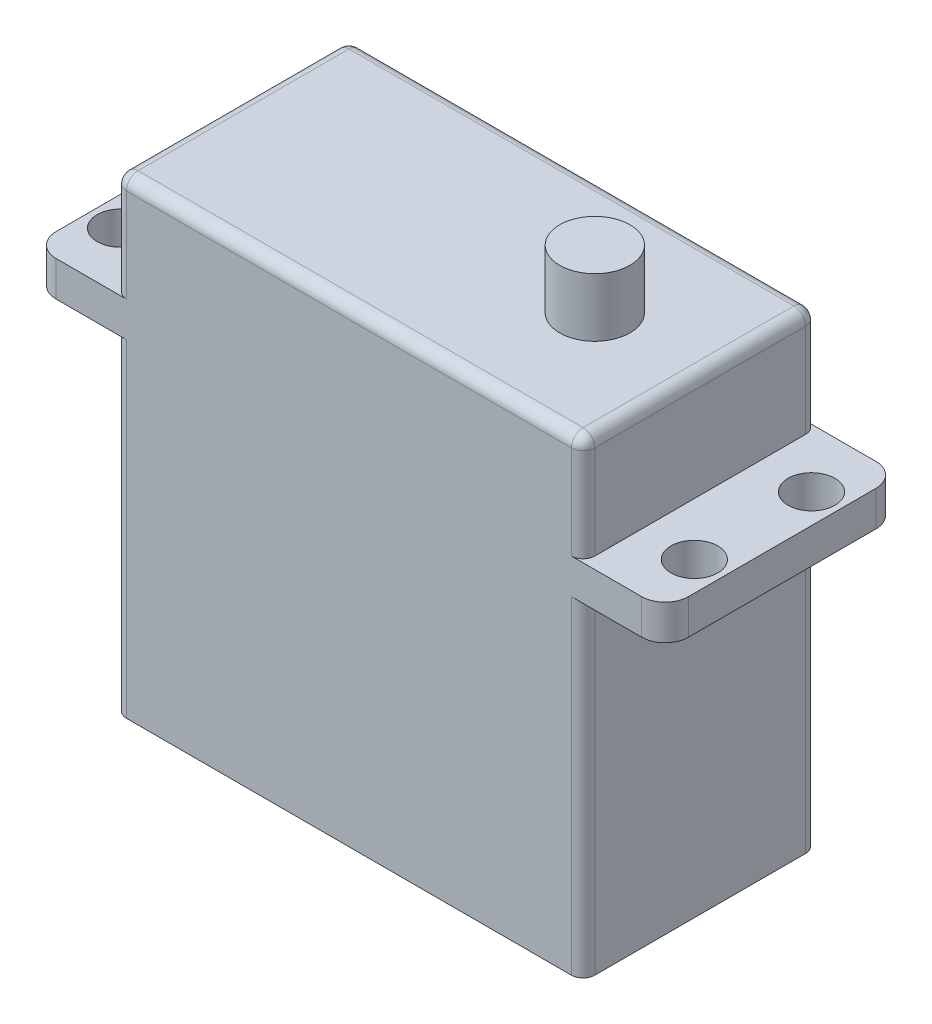
SolidWorks part; units mm, degrees
ref_plane "Front Plane" through (0, 0, 0) normal (0, 0, 1) x (1, 0, 0)
ref_plane "Top Plane" through (0, 0, 0) normal (0, 1, 0) x (1, 0, 0)
ref_plane "Right Plane" through (0, 0, 0) normal (1, 0, 0) x (0, 0, -1)
sketch "Sketch1" plane through (0, 0, 0) normal (0, 0, 1) x (1, 0, 0)
  line L0 (20, 14) -> (27, 14)
  line L2 (-20, 14) -> (-20, -14)
  line L3 (-20, -14) -> (20, -14)
  line L4 (20, 14) -> (20, -14)
  line L5 (20, 17) -> (27, 17)
  line L7 (-27, 14) -> (-20, 14)
  line L8 (-27, 14) -> (-27, 17)
  line L9 (-27, 17) -> (-20, 17)
  line L10 (27, 14) -> (27, 17)
  line L11 (-20, 17) -> (-20, 25)
  line L12 (-19, 26) -> (19, 26)
  line L13 (20, 17) -> (20, 25)
  arc A0 (19, 26) -> (20, 25) centre (19, 25) cw
  arc A1 (-20, 25) -> (-19, 26) centre (-19, 25) cw
  point P0 (0, 0)
  point P18 (-20, 26)
  dimension "D8" = 1
  dimension "D1" = 40
  dimension "D2" = 28
  dimension "D3" = 7
  dimension "D4" = 7
  dimension "D5" = 3
  dimension "D6" = 9
  dimension "D7" = 40
extrude "Boss-Extrude1" add sketch "Sketch1" along normal blind 20
sketch "Sketch2" plane through (0, 17, 0) normal (0, 1, 0) x (1, 0, 0)
  line L0 (19, 0) -> (-19, 0) construction
  line L1 (-27, -20) -> (-27, 0) construction
  circle A0 centre (-24.5, -5) radius 2
  circle A1 centre (-24.5, -15) radius 2
  dimension "D2" = 4
  dimension "D3" = 4
  dimension "D1" = 10
  dimension "D4" = 5
  dimension "D5" = 2.5
  dimension "D6" = 2.5
extrude "Cut-Extrude1" cut sketch "Sketch2" against normal blind 20
mirror "Mirror1" about plane through (0, 0, 0) normal (1, 0, 0) of "Cut-Extrude1"
fillet "Fillet1" radius 2 4 edges at (27, 15.5, 0) (27, 15.5, 20) (-27, 15.5, 0) (-27, 15.5, 20)
fillet "Fillet2" radius 1 14 edges at (-20, 21, 0) (-19.7071, 25.7071, 0) (0, 26, 0) (19.7071, 25.7071, 0) (-20, 21, 20) (-19.7071, 25.7071, 20) (0, 26, 20) (19.7071, 25.7071, 20) (-20, 0, 0) (20, 21, 0) (20, 0, 0) (20, 21, 20) (20, 0, 20) (-20, 0, 20)
sketch "Sketch3" plane through (0, 26, 0) normal (0, 1, 0) x (1, 0, 0)
  line L0 (20, -19) -> (20, -1) construction
  line L3 (20, -19) -> (20, -1) construction
  circle A0 centre (11, -10) radius 3
  dimension "D1" = 6
  dimension "D2" = 9
  dimension "D3" = 6
extrude "Boss-Extrude2" add sketch "Sketch3" along normal blind 5
